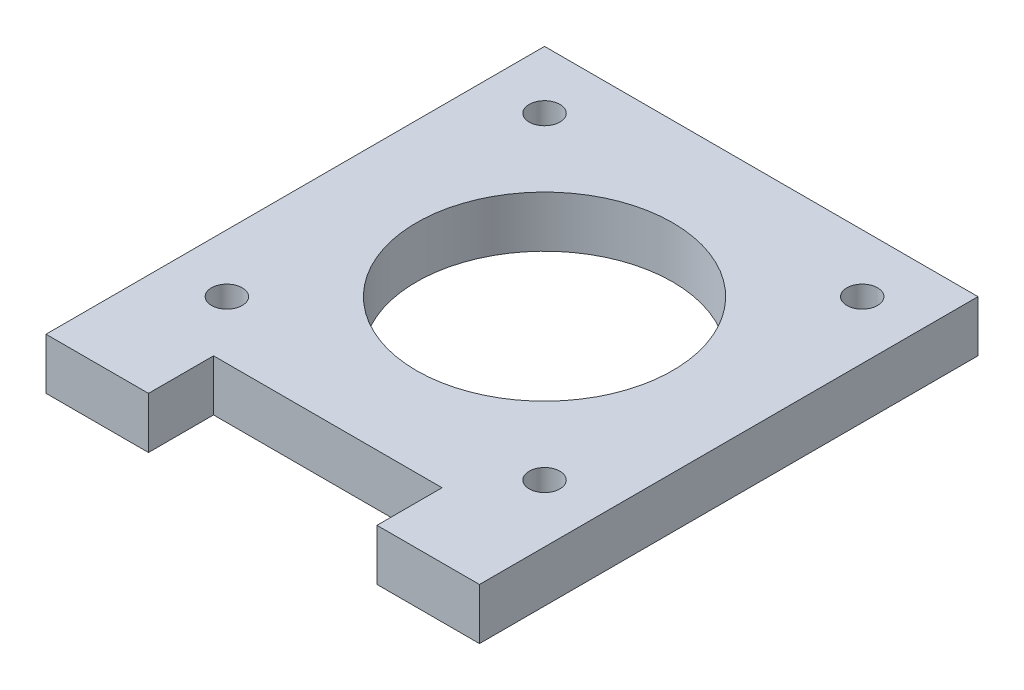
SolidWorks part; units mm, degrees
ref_plane "Front Plane" through (0, 0, 0) normal (0, 0, 1) x (1, 0, 0)
ref_plane "Top Plane" through (0, 0, 0) normal (0, 1, 0) x (1, 0, 0)
ref_plane "Right Plane" through (0, 0, 0) normal (1, 0, 0) x (0, 0, -1)
sketch "Sketch1" plane through (0, 0, 0) normal (0, 1, 0) x (1, 0, 0)
  line L0 (-21.15, -21.15) -> (-21.15, -27.5)
  line L1 (-15.5, -15.5) -> (15.5, -15.5) construction
  line L2 (-15.5, -15.5) -> (-15.5, 15.5) construction
  line L3 (-15.5, 15.5) -> (15.5, 15.5) construction
  line L4 (15.5, -15.5) -> (15.5, 15.5) construction
  line L5 (-15.5, -15.5) -> (15.5, 15.5) construction
  line L6 (-15.5, 15.5) -> (15.5, -15.5) construction
  line L7 (-21.15, -21.15) -> (21.15, -21.15) construction
  line L8 (-21.15, -21.15) -> (-21.15, 21.15)
  line L9 (-21.15, 21.15) -> (21.15, 21.15)
  line L10 (21.15, -21.15) -> (21.15, 21.15)
  line L11 (-21.15, -21.15) -> (21.15, 21.15) construction
  line L12 (-21.15, 21.15) -> (21.15, -21.15) construction
  line L13 (-21.15, -27.5) -> (-11.15, -27.5)
  line L14 (-11.15, -27.5) -> (-11.15, -21.15)
  line L15 (-11.15, -21.15) -> (11.15, -21.15)
  line L16 (11.15, -21.15) -> (11.15, -27.5)
  line L17 (11.15, -27.5) -> (21.15, -27.5)
  line L18 (21.15, -27.5) -> (21.15, -21.15)
  circle A0 centre (0, 0) radius 12.5
  circle A1 centre (-15.5, 15.5) radius 1.5
  circle A2 centre (15.5, 15.5) radius 1.5
  circle A3 centre (15.5, -15.5) radius 1.5
  circle A4 centre (-15.5, -15.5) radius 1.5
  point P0 (0, 0)
  dimension "D2" = 3
  dimension "D3" = 25
  dimension "D1" = 31
  dimension "D4" = 42.3
  dimension "D5" = 6.35
  dimension "D6" = 10
extrude "Boss-Extrude1" add sketch "Sketch1" along normal mid plane 5
